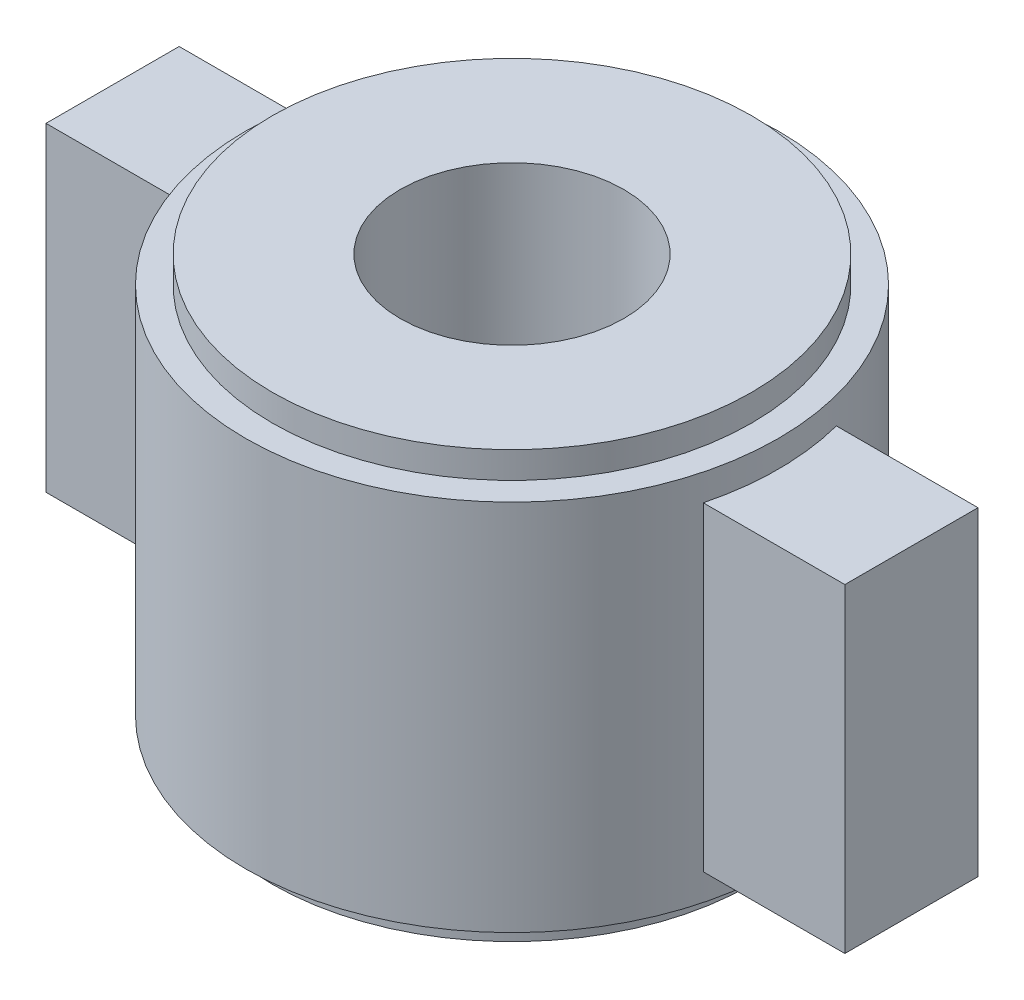
SolidWorks part; units mm, degrees
ref_plane "前视基准面" through (0, 0, 0) normal (0, 0, 1) x (1, 0, 0)
ref_plane "上视基准面" through (0, 0, 0) normal (0, 1, 0) x (1, 0, 0)
ref_plane "右视基准面" through (0, 0, 0) normal (1, 0, 0) x (0, 0, -1)
other "Configuration Table"
sketch "草图1" plane through (0, 0, 0) normal (0, 0, 1) x (1, 0, 0)
  line L0 (4.2, 0) -> (9, 0)
  line L1 (9, 0) -> (9, 1)
  line L2 (9, 1) -> (10, 1)
  line L3 (10, 1) -> (10, 15)
  line L4 (10, 15) -> (9, 15)
  line L5 (9, 15) -> (9, 16)
  line L6 (9, 16) -> (4.2, 16)
  line L7 (4.2, 16) -> (4.2, 0)
  line L8 (0, 0) -> (0, 16) construction
  dimension "x0" = 4.2
  dimension "x1" = 9
  dimension "x3" = 10
  dimension "x5" = 9
  dimension "y2" = 1
  dimension "y4" = 15
  dimension "y6" = 16
  dimension "y9" = 16
revolve "Round_nut" add sketch "草图1" angle 360 about L8
ref_plane "Tongue_plane" through (0, 0, -2.5) normal (0, 0, 1) x (1, 0, 0)
sketch "草图3" plane through (0, 0, -2.5) normal (0, 0, 1) x (1, 0, 0)
  line L0 (-8, 2) -> (-15, 2)
  line L1 (-15, 2) -> (-15, 14)
  line L2 (-15, 14) -> (-8, 14)
  line L3 (-8, 14) -> (-8, 2)
  dimension "x0" = 8
  dimension "x1" = 15
  dimension "y0" = 2
  dimension "y2" = 14
extrude "Continuous_tongue" add sketch "草图3" along normal blind 5
sketch "草图4" plane through (0, 0, -2.5) normal (0, 0, 1) x (1, 0, 0)
  line L0 (8, 2) -> (15, 2)
  line L1 (15, 2) -> (15, 14)
  line L2 (15, 14) -> (8, 14)
  line L3 (8, 14) -> (8, 2)
  dimension "x0" = 8
  dimension "x1" = 15
  dimension "y0" = 2
  dimension "y2" = 14
extrude "凸台-拉伸2" add sketch "草图4" along normal blind 5
